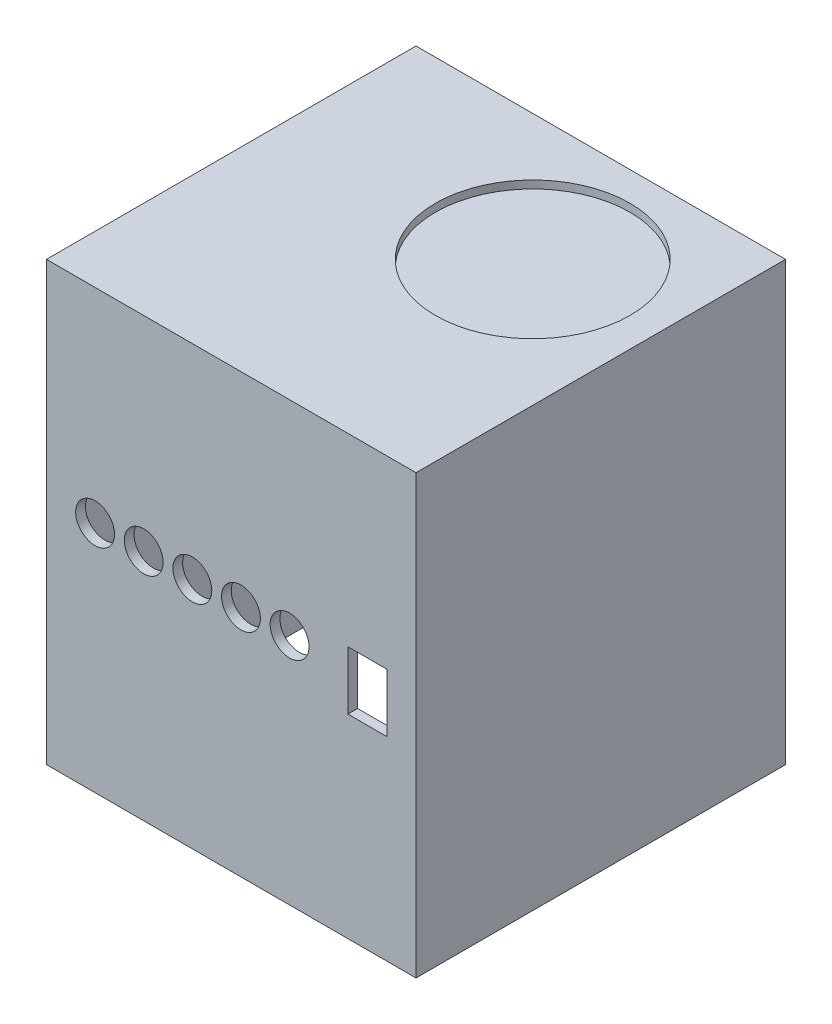
SolidWorks part; units mm, degrees
ref_plane "Front Plane" through (0, 0, 0) normal (0, 0, 1) x (1, 0, 0)
ref_plane "Top Plane" through (0, 0, 0) normal (0, 1, 0) x (1, 0, 0)
ref_plane "Right Plane" through (0, 0, 0) normal (1, 0, 0) x (0, 0, -1)
sketch "Sketch2" plane through (0, 0, 0) normal (0, 1, 0) x (1, 0, 0)
  line L1 (-45, -45) -> (45, -45)
  line L2 (-45, -45) -> (-45, 45)
  line L3 (-45, 45) -> (45, 45)
  line L4 (45, -45) -> (45, 45)
  point P4 (120.5184, 130.6024)
  point P5 (-7.9938, -7.9938)
  point P6 (44.4898, 45.2169)
extrude "Boss-Extrude2" add sketch "Sketch2" along normal blind 110
shell "Shell2" thickness 2.5
sketch "Sketch3" plane through (0, 0, 47.5) normal (0, 0, 1) x (1, 0, 0)
  line L1 (30, 65) -> (40, 65)
  line L2 (30, 65) -> (30, 50)
  line L3 (30, 50) -> (40, 50)
  line L4 (40, 65) -> (40, 50)
  circle A0 centre (-35, 60) radius 5
  circle A1 centre (-22.5, 60) radius 5
  circle A2 centre (-10, 60) radius 5
  circle A3 centre (2.5, 60) radius 5
  circle A4 centre (15, 60) radius 5
  point P14 (39.43, 66.3298)
  point P15 (17.788, 53.1371)
  point P16 (0, 0)
  point P17 (0, 0)
  point P18 (0, 0)
  point P19 (0, 0)
  point P20 (0, 0)
  point P21 (0, 0)
  point P22 (0, 0)
extrude "Cut-Extrude1" cut sketch "Sketch3" against normal blind 10
sketch "Sketch4" plane through (0, 112.5, 0) normal (0, 1, 0) x (1, 0, 0)
  circle A0 centre (15, 15) radius 25
extrude "Cut-Extrude2" cut sketch "Sketch4" against normal blind 2
